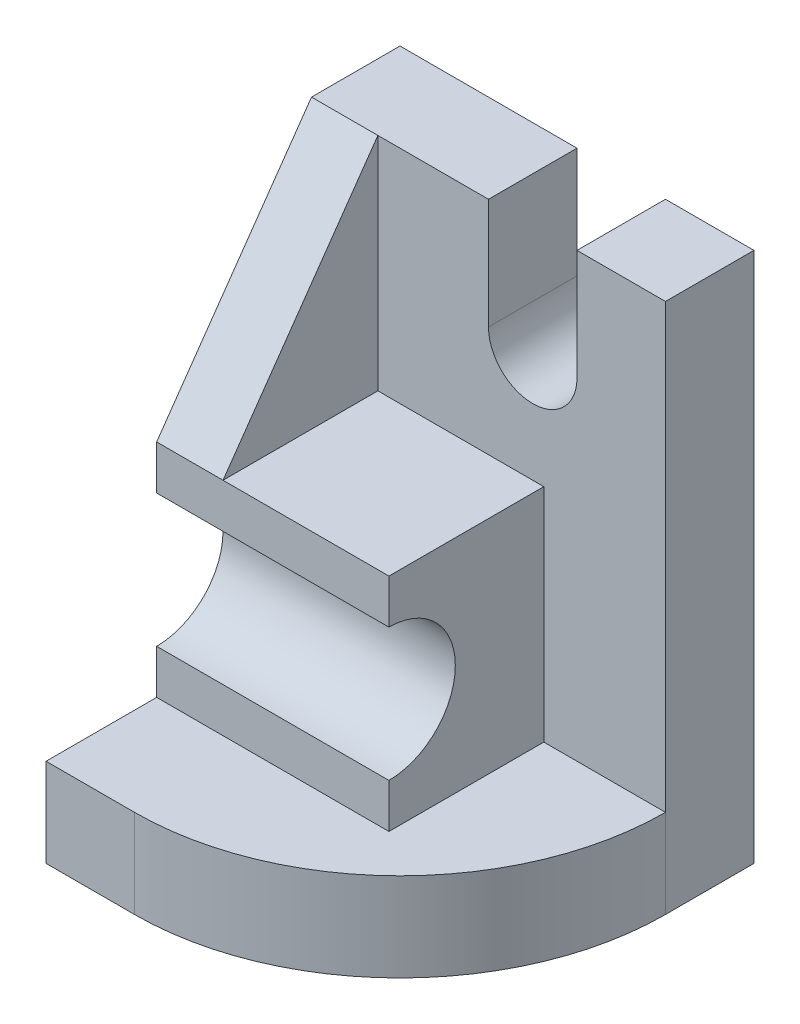
SolidWorks part; units mm, degrees
ref_plane "Plan de face" through (0, 0, 0) normal (1, 0, 0) x (0, 1, 0)
ref_plane "Plan de dessus" through (0, 0, 0) normal (0, 0, 1) x (0, 1, 0)
ref_plane "Plan de droite" through (0, 0, 0) normal (0, 1, 0) x (-1, 0, 0)
sketch "Esquisse1" plane through (0, 0, 0) normal (0, 0, 1) x (0, 1, 0)
  line L1 (0, 0) -> (96, 0)
  line L2 (0, 0) -> (0, 64)
  line L3 (0, 64) -> (96, 64)
  line L4 (96, 0) -> (96, 64)
  dimension "D1" = 96
  dimension "D2" = 64
extrude "Boss.-Extru.1" add sketch "Esquisse1" along normal blind 16
sketch "Esquisse2" plane through (0, 0, 16) normal (0, 0, 1) x (1, 0, 0)
  line L1 (-24, 96) -> (-24, 76) construction
  line L2 (0, 96) -> (-64, 96) construction
  line L3 (-16, 96) -> (-16, 76)
  line L4 (-32, 96) -> (-32, 76)
  arc A0 (-16, 96) -> (-32, 96) centre (-24, 96) ccw
  arc A1 (-32, 76) -> (-16, 76) centre (-24, 76) ccw
  point P0 (-24, 86)
  dimension "D1" = 20
  dimension "D2" = 16
  dimension "D3" = 16
extrude "Enlèv. mat.-Extru.2" cut sketch "Esquisse2" against normal through all
sketch "Esquisse4" plane through (0, 0, 0) normal (0, -1, 0) x (1, 0, 0)
  line L1 (-64, 0) -> (0, 0)
  line L2 (-64, 0) -> (-64, 64)
  line L3 (-64, 64) -> (-48, 64)
  line L4 (0, 0) -> (0, 16)
  arc A0 (0, 16) -> (-48, 64) centre (-48, 16) ccw
  point P7 (0, 64)
  dimension "D3" = 48
  dimension "D1" = 64
  dimension "D2" = 64
extrude "Boss.-Extru.2" add sketch "Esquisse4" against normal blind 16
sketch "Esquisse5" plane through (0, 0, 16) normal (0, 0, 1) x (1, 0, 0)
  line L0 (0, 16) -> (0, 96) construction
  line L1 (-64, 16) -> (-22, 16)
  line L2 (-64, 16) -> (-64, 56)
  line L3 (-64, 56) -> (-22, 56)
  line L4 (-22, 16) -> (-22, 56)
  dimension "D1" = 22
  dimension "D2" = 40
extrude "Boss.-Extru.3" add sketch "Esquisse5" along normal blind 28
sketch "Esquisse7" plane through (-22, 0, 0) normal (1, 0, 0) x (0, 1, 0)
  line L0 (16, 44) -> (56, 44) construction
  circle A0 centre (36, 44) radius 12
  dimension "D1" = 24
extrude "Enlèv. mat.-Extru.4" cut sketch "Esquisse7" against normal up to next
sketch "Esquisse8" plane through (-64, 0, 0) normal (-1, 0, 0) x (0, -1, 0)
  line L0 (-56, 44) -> (-96, 16)
  line L10 (-16, 44) -> (-24, 44)
  line L11 (-48, 44) -> (-56, 44)
  line L12 (-56, 44) -> (-56, 16)
  line L13 (-56, 16) -> (-96, 16)
  line L14 (-96, 16) -> (-96, 0)
  line L15 (-96, 0) -> (0, 0)
  line L16 (0, 0) -> (0, 64)
  line L17 (0, 64) -> (-16, 64)
  line L18 (-16, 64) -> (-16, 44)
  line L21 (-56, 44) -> (-56, 16)
  line L22 (-56, 16) -> (-96, 16)
  arc A1 (-48, 44) -> (-24, 44) centre (-36, 44) ccw
  dimension "D1" = 0
extrude "Boss.-Extru.4" add sketch "Esquisse8" against normal blind 12
